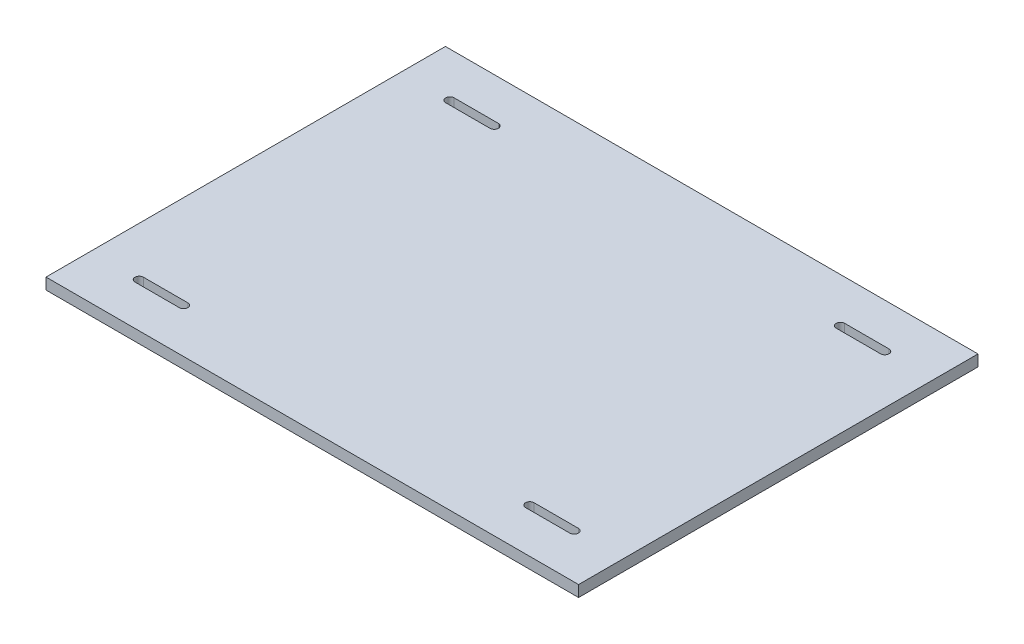
SolidWorks part; units mm, degrees
ref_plane "Alzado" through (0, 0, 0) normal (0, 0, 1) x (1, 0, 0)
ref_plane "Planta" through (0, 0, 0) normal (0, 1, 0) x (1, 0, 0)
ref_plane "Vista lateral" through (0, 0, 0) normal (1, 0, 0) x (0, 0, -1)
sketch "Croquis1" plane through (0, 0, 0) normal (0, 1, 0) x (1, 0, 0)
  line L1 (-600, -450) -> (600, -450)
  line L2 (-600, -450) -> (-600, 450)
  line L3 (-600, 450) -> (600, 450)
  line L4 (600, -450) -> (600, 450)
  line L5 (-600, -450) -> (600, 450) construction
  line L6 (-600, 450) -> (600, -450) construction
  point P0 (0, 0)
  dimension "D1" = 1200
  dimension "D2" = 900
extrude "Saliente-Extruir1" add sketch "Croquis1" along normal blind 25.4
sketch "Croquis2" plane through (0, 25.4, 0) normal (0, 1, 0) x (1, 0, 0)
  line L0 (0, 450) -> (0, 0) construction
  line L1 (600, 450) -> (-600, 450) construction
  line L2 (0, 0) -> (600, 0) construction
  line L3 (600, -450) -> (600, 450) construction
  line L4 (-390, 340.475) -> (-490, 359.525) construction
  line L5 (390, 359.525) -> (490, 359.525)
  line L6 (-390, 359.525) -> (-490, 340.475) construction
  line L7 (390, 340.475) -> (490, 340.475)
  line L8 (-390, 340.475) -> (-490, 340.475)
  line L9 (390, 359.525) -> (490, 340.475) construction
  line L10 (390, 340.475) -> (490, 359.525) construction
  line L11 (-390, 359.525) -> (-490, 359.525)
  line L12 (390, -340.475) -> (490, -359.525) construction
  line L13 (390, -359.525) -> (490, -340.475) construction
  line L14 (-390, -359.525) -> (-490, -340.475) construction
  line L15 (-390, -340.475) -> (-490, -359.525) construction
  line L16 (-390, -359.525) -> (-490, -359.525)
  line L17 (-390, -340.475) -> (-490, -340.475)
  line L18 (390, -340.475) -> (490, -340.475)
  line L19 (390, -359.525) -> (490, -359.525)
  arc A0 (390, 359.525) -> (390, 340.475) centre (390, 350) ccw
  arc A1 (490, 359.525) -> (490, 340.475) centre (490, 350) cw
  arc A2 (-490, 359.525) -> (-490, 340.475) centre (-490, 350) ccw
  arc A3 (-390, 359.525) -> (-390, 340.475) centre (-390, 350) cw
  arc A4 (-390, -359.525) -> (-390, -340.475) centre (-390, -350) ccw
  arc A5 (-490, -359.525) -> (-490, -340.475) centre (-490, -350) cw
  arc A6 (490, -359.525) -> (490, -340.475) centre (490, -350) ccw
  arc A7 (390, -359.525) -> (390, -340.475) centre (390, -350) cw
  point P5 (440, 350)
  point P21 (-440, 350)
  point P34 (-440, -350)
  point P35 (440, -350)
  dimension "D1" = 19.05
  dimension "D2" = 100
  dimension "D3" = 160
  dimension "D4" = 100
extrude "Cortar-Extruir1" cut sketch "Croquis2" against normal blind 25.4
